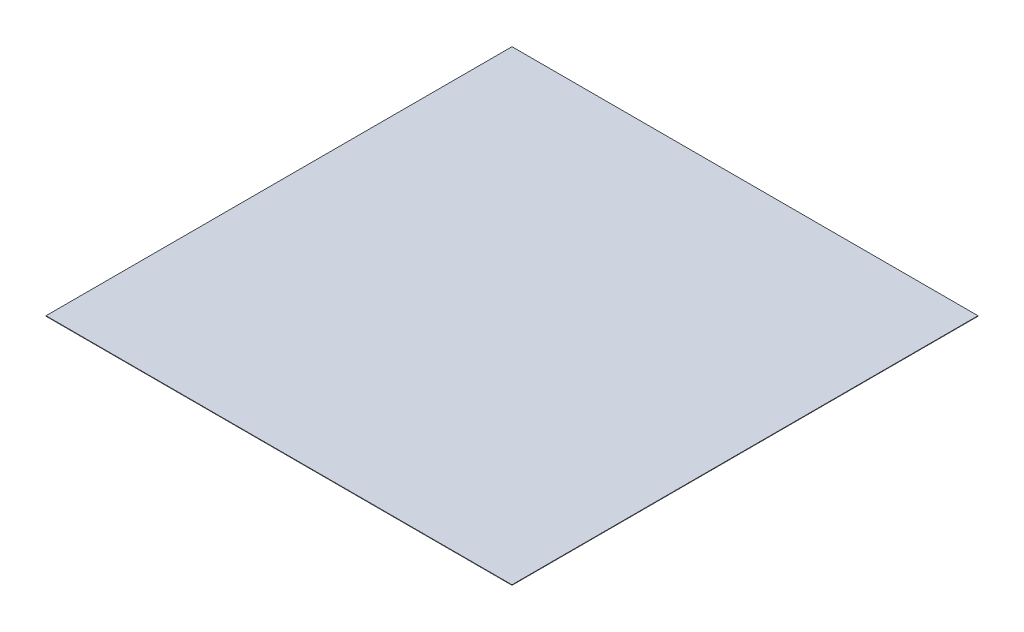
SolidWorks part; units mm, degrees
ref_plane "Front Plane" through (0, 0, 0) normal (0, 0, 1) x (1, 0, 0)
ref_plane "Top Plane" through (0, 0, 0) normal (0, 1, 0) x (1, 0, 0)
ref_plane "Right Plane" through (0, 0, 0) normal (1, 0, 0) x (0, 0, -1)
sketch "Sketch1" plane through (0, 0, 0) normal (0, 1, 0) x (1, 0, 0)
  line L1 (-101.6, -101.6) -> (101.6, -101.6)
  line L2 (-101.6, -101.6) -> (-101.6, 101.6)
  line L3 (-101.6, 101.6) -> (101.6, 101.6)
  line L4 (101.6, -101.6) -> (101.6, 101.6)
  line L5 (-101.6, -101.6) -> (101.6, 101.6) construction
  line L6 (-101.6, 101.6) -> (101.6, -101.6) construction
  point P0 (0, 0)
  dimension "D1" = 203.2
  dimension "D2" = 203.2
extrude "Boss-Extrude1" add sketch "Sketch1" along normal blind 0.2032 contours L1 L4 L3 L2
